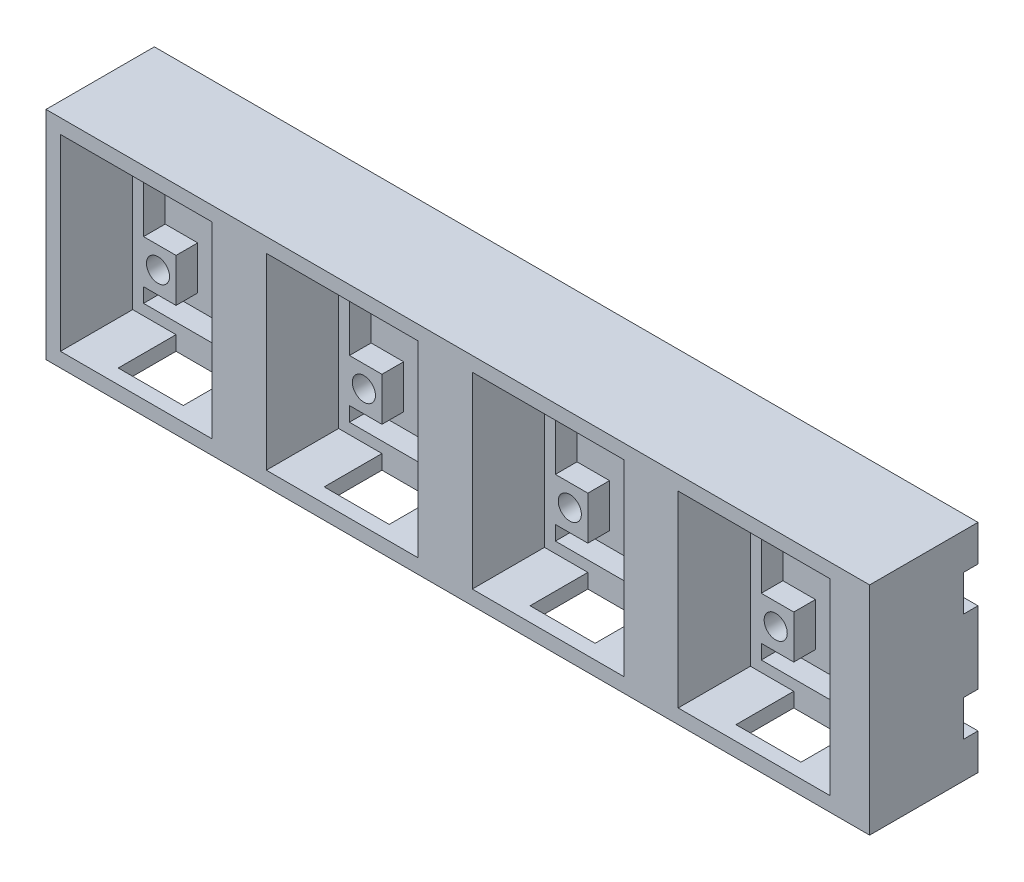
SolidWorks part; units mm, degrees
ref_plane "正面" through (0, 0, 0) normal (0, 0, 1) x (1, 0, 0)
ref_plane "平面" through (0, 0, 0) normal (0, 1, 0) x (1, 0, 0)
ref_plane "右側面" through (0, 0, 0) normal (1, 0, 0) x (0, 0, -1)
sketch "ｽｹｯﾁ1" plane through (0, 0, 0) normal (0, 0, 1) x (1, 0, 0)
  line L1 (-83.9031, 40.6786) -> (30.0969, 40.6786)
  line L2 (-83.9031, 40.6786) -> (-83.9031, 10.6786)
  line L3 (-83.9031, 10.6786) -> (30.0969, 10.6786)
  line L4 (30.0969, 40.6786) -> (30.0969, 10.6786)
  dimension "D1" = 30
extrude "ﾎﾞｽ - 押し出し1" add sketch "ｽｹｯﾁ1" along normal blind 15
sketch "ｽｹｯﾁ2" plane through (0, 0, 15) normal (0, 0, 1) x (1, 0, 0)
  line L0 (30.0969, 40.6786) -> (-83.9031, 40.6786) construction
  line L1 (-81.9031, 38.6786) -> (-60.9031, 38.6786)
  line L2 (-81.9031, 38.6786) -> (-81.9031, 12.6786)
  line L3 (-81.9031, 12.6786) -> (-60.9031, 12.6786)
  line L4 (-60.9031, 38.6786) -> (-60.9031, 12.6786)
  line L5 (-83.9031, 10.6786) -> (30.0969, 10.6786) construction
  line L7 (-83.9031, 40.6786) -> (-83.9031, 10.6786) construction
  line L8 (-58.9031, 40.6786) -> (-58.9031, 10.6786) construction
  line L9 (-55.4031, 40.6786) -> (-55.4031, 10.6786) construction
  line L10 (-30.4031, 40.6786) -> (-30.4031, 10.6786) construction
  line L11 (-26.9031, 40.6786) -> (-26.9031, 10.6786) construction
  line L12 (-1.9031, 40.6786) -> (-1.9031, 10.6786) construction
  line L13 (1.5969, 40.6786) -> (1.5969, 10.6786) construction
  line L14 (26.5969, 40.6786) -> (26.5969, 10.6786) construction
  line L16 (30.0969, 10.6786) -> (30.0969, 40.6786) construction
  line L18 (-53.4031, 38.6786) -> (-32.4031, 38.6786)
  line L19 (-53.4031, 38.6786) -> (-53.4031, 12.6786)
  line L20 (-53.4031, 12.6786) -> (-32.4031, 12.6786)
  line L21 (-32.4031, 38.6786) -> (-32.4031, 12.6786)
  line L22 (-24.9031, 38.6786) -> (-3.9031, 38.6786)
  line L23 (-24.9031, 38.6786) -> (-24.9031, 12.6786)
  line L24 (-24.9031, 12.6786) -> (-3.9031, 12.6786)
  line L25 (-3.9031, 38.6786) -> (-3.9031, 12.6786)
  line L26 (3.5969, 38.6786) -> (24.5969, 38.6786)
  line L27 (3.5969, 38.6786) -> (3.5969, 12.6786)
  line L28 (3.5969, 12.6786) -> (24.5969, 12.6786)
  line L29 (24.5969, 38.6786) -> (24.5969, 12.6786)
  dimension "D1" = 26
  dimension "D2" = 21
  dimension "D3" = 2
  dimension "D4" = 2
  dimension "D5" = 2
  dimension "D6" = 2
  dimension "D7" = 25
  dimension "D8" = 3.5
  dimension "D9" = 25
  dimension "D10" = 3.5
  dimension "D11" = 25
  dimension "D12" = 3.5
  dimension "D13" = 25
  dimension "D14" = 3.5
  dimension "D15" = 2
  dimension "D16" = 21
  dimension "D17" = 2
  dimension "D18" = 21
  dimension "D19" = 2
  dimension "D20" = 21
  dimension "D21" = 2
  dimension "D22" = 2
  dimension "D23" = 2
extrude "ｶｯﾄ - 押し出し1" cut sketch "ｽｹｯﾁ2" against normal blind 13
sketch "ｽｹｯﾁ3" plane through (0, 0, 2) normal (0, 0, 1) x (1, 0, 0)
  line L0 (-53.4031, 38.6786) -> (-53.4031, 12.6786) construction
  line L1 (-60.9031, 38.6786) -> (-81.9031, 38.6786)
  line L2 (-60.9031, 38.6786) -> (-60.9031, 12.6786)
  line L3 (-60.9031, 12.6786) -> (-81.9031, 12.6786)
  line L4 (-81.9031, 38.6786) -> (-81.9031, 12.6786)
  line L5 (-80.4031, 37.1786) -> (-62.4031, 37.1786)
  line L6 (-80.4031, 37.1786) -> (-80.4031, 14.1786)
  line L7 (-80.4031, 14.1786) -> (-62.4031, 14.1786)
  line L8 (-62.4031, 37.1786) -> (-62.4031, 14.1786)
  line L9 (-51.9031, 37.1786) -> (-33.9031, 37.1786)
  line L10 (-51.9031, 37.1786) -> (-51.9031, 14.1786)
  line L11 (-51.9031, 14.1786) -> (-33.9031, 14.1786)
  line L12 (-33.9031, 37.1786) -> (-33.9031, 14.1786)
  line L13 (-23.4031, 37.1786) -> (-5.4031, 37.1786)
  line L14 (-23.4031, 37.1786) -> (-23.4031, 14.1786)
  line L15 (-23.4031, 14.1786) -> (-5.4031, 14.1786)
  line L16 (-5.4031, 37.1786) -> (-5.4031, 14.1786)
  line L17 (5.0969, 37.1786) -> (23.0969, 37.1786)
  line L18 (5.0969, 37.1786) -> (5.0969, 14.1786)
  line L19 (5.0969, 14.1786) -> (23.0969, 14.1786)
  line L20 (23.0969, 37.1786) -> (23.0969, 14.1786)
  line L21 (-24.9031, 38.6786) -> (-24.9031, 12.6786) construction
  line L22 (3.5969, 38.6786) -> (3.5969, 12.6786) construction
  line L24 (-53.4031, 38.6786) -> (-32.4031, 38.6786)
  line L25 (-53.4031, 38.6786) -> (-53.4031, 12.6786)
  line L26 (-53.4031, 12.6786) -> (-32.4031, 12.6786)
  line L27 (-32.4031, 38.6786) -> (-32.4031, 12.6786)
  line L28 (-24.9031, 38.6786) -> (-3.9031, 38.6786)
  line L29 (-24.9031, 38.6786) -> (-24.9031, 12.6786)
  line L30 (-24.9031, 12.6786) -> (-3.9031, 12.6786)
  line L31 (-3.9031, 38.6786) -> (-3.9031, 12.6786)
  line L32 (3.5969, 38.6786) -> (24.5969, 38.6786)
  line L33 (3.5969, 38.6786) -> (3.5969, 12.6786)
  line L34 (3.5969, 12.6786) -> (24.5969, 12.6786)
  line L35 (24.5969, 38.6786) -> (24.5969, 12.6786)
  dimension "D1" = 1.5
  dimension "D2" = 1.5
  dimension "D3" = 1.5
  dimension "D4" = 1.5
  dimension "D5" = 1.5
  dimension "D6" = 1.5
  dimension "D7" = 1.5
  dimension "D8" = 26
  dimension "D9" = 21
  dimension "D10" = 26
  dimension "D11" = 21
  dimension "D12" = 26
  dimension "D13" = 21
extrude "ﾎﾞｽ - 押し出し2" add sketch "ｽｹｯﾁ3" along normal blind 3
sketch "ｽｹｯﾁ5" plane through (0, 0, 2) normal (0, 0, 1) x (1, 0, 0)
  line L0 (-62.4031, 14.1786) -> (-62.4031, 37.1786) construction
  line L1 (-62.4031, 22.1786) -> (-66.9031, 22.1786)
  line L2 (-62.4031, 22.1786) -> (-62.4031, 16.1786)
  line L3 (-62.4031, 16.1786) -> (-66.9031, 16.1786)
  line L4 (-66.9031, 22.1786) -> (-66.9031, 16.1786)
  line L5 (-51.9031, 37.1786) -> (-51.9031, 14.1786) construction
  line L6 (-81.9031, 12.6786) -> (-60.9031, 12.6786) construction
  line L7 (-80.4031, 37.1786) -> (-80.4031, 14.1786) construction
  line L8 (-80.4031, 22.1786) -> (-75.9031, 22.1786)
  line L9 (-80.4031, 22.1786) -> (-80.4031, 16.1786)
  line L10 (-80.4031, 16.1786) -> (-75.9031, 16.1786)
  line L11 (-75.9031, 22.1786) -> (-75.9031, 16.1786)
  line L12 (-51.9031, 22.1786) -> (-47.4031, 22.1786)
  line L13 (-51.9031, 22.1786) -> (-51.9031, 16.1786)
  line L14 (-51.9031, 16.1786) -> (-47.4031, 16.1786)
  line L15 (-47.4031, 22.1786) -> (-47.4031, 16.1786)
  line L16 (-33.9031, 14.1786) -> (-33.9031, 37.1786) construction
  line L17 (-33.9031, 22.1786) -> (-38.4031, 22.1786)
  line L18 (-33.9031, 22.1786) -> (-33.9031, 16.1786)
  line L19 (-33.9031, 16.1786) -> (-38.4031, 16.1786)
  line L20 (-38.4031, 22.1786) -> (-38.4031, 16.1786)
  line L21 (-23.4031, 37.1786) -> (-23.4031, 14.1786) construction
  line L22 (-23.4031, 22.1786) -> (-18.9031, 22.1786)
  line L23 (-23.4031, 22.1786) -> (-23.4031, 16.1786)
  line L24 (-23.4031, 16.1786) -> (-18.9031, 16.1786)
  line L25 (-18.9031, 22.1786) -> (-18.9031, 16.1786)
  line L26 (-5.4031, 14.1786) -> (-5.4031, 37.1786) construction
  line L27 (-5.4031, 22.1786) -> (-9.9031, 22.1786)
  line L28 (-5.4031, 22.1786) -> (-5.4031, 16.1786)
  line L29 (-5.4031, 16.1786) -> (-9.9031, 16.1786)
  line L30 (-9.9031, 22.1786) -> (-9.9031, 16.1786)
  line L31 (5.0969, 37.1786) -> (5.0969, 14.1786) construction
  line L32 (5.0969, 22.1786) -> (9.5969, 22.1786)
  line L33 (5.0969, 22.1786) -> (5.0969, 16.1786)
  line L34 (5.0969, 16.1786) -> (9.5969, 16.1786)
  line L35 (9.5969, 22.1786) -> (9.5969, 16.1786)
  line L36 (23.0969, 14.1786) -> (23.0969, 37.1786) construction
  line L37 (23.0969, 22.1786) -> (18.5969, 22.1786)
  line L38 (23.0969, 22.1786) -> (23.0969, 16.1786)
  line L39 (23.0969, 16.1786) -> (18.5969, 16.1786)
  line L40 (18.5969, 22.1786) -> (18.5969, 16.1786)
  point P10 (-66.9031, 19.1786)
  point P15 (-75.9031, 19.1786)
  dimension "D1" = 4.5
  dimension "D2" = 6
  dimension "D3" = 6.5
  dimension "D4" = 6.5
extrude "ﾎﾞｽ - 押し出し3" add sketch "ｽｹｯﾁ5" along normal blind 3
sketch "ｽｹｯﾁ6" plane through (0, 0, 5) normal (0, 0, 1) x (1, 0, 0)
  line L0 (-66.9031, 22.1786) -> (-66.9031, 16.1786) construction
  line L1 (-66.9031, 16.1786) -> (-62.4031, 16.1786) construction
  line L2 (-75.9031, 16.1786) -> (-75.9031, 22.1786) construction
  line L3 (-80.4031, 16.1786) -> (-75.9031, 16.1786) construction
  line L4 (-47.4031, 16.1786) -> (-47.4031, 22.1786) construction
  line L5 (-51.9031, 16.1786) -> (-47.4031, 16.1786) construction
  line L6 (-38.4031, 22.1786) -> (-38.4031, 16.1786) construction
  line L7 (-38.4031, 16.1786) -> (-33.9031, 16.1786) construction
  line L8 (-18.9031, 16.1786) -> (-18.9031, 22.1786) construction
  line L9 (-23.4031, 16.1786) -> (-18.9031, 16.1786) construction
  line L10 (-9.9031, 22.1786) -> (-9.9031, 16.1786) construction
  line L11 (-9.9031, 16.1786) -> (-5.4031, 16.1786) construction
  line L12 (9.5969, 16.1786) -> (9.5969, 22.1786) construction
  line L13 (5.0969, 16.1786) -> (9.5969, 16.1786) construction
  line L14 (18.5969, 22.1786) -> (18.5969, 16.1786) construction
  line L15 (18.5969, 16.1786) -> (23.0969, 16.1786) construction
  circle A0 centre (-64.4031, 19.1786) radius 1.6
  circle A1 centre (-78.4031, 19.1786) radius 1.6
  circle A2 centre (-49.9031, 19.1786) radius 1.6
  circle A3 centre (-35.9031, 19.1786) radius 1.6
  circle A4 centre (-21.4031, 19.1786) radius 1.6
  circle A5 centre (-7.4031, 19.1786) radius 1.6
  circle A6 centre (7.0969, 19.1786) radius 1.6
  circle A7 centre (21.0969, 19.1786) radius 1.6
  dimension "D1" = 3.2
  dimension "D4" = 2.5
  dimension "D5" = 3
  dimension "D6" = 2.5
  dimension "D2" = 2.5
  dimension "D3" = 3
  dimension "D7" = 3
  dimension "D8" = 2.5
  dimension "D9" = 3
  dimension "D10" = 2.5
  dimension "D11" = 3
  dimension "D12" = 2.5
  dimension "D13" = 3
  dimension "D14" = 2.5
  dimension "D15" = 3
  dimension "D16" = 2.5
  dimension "D17" = 3
extrude "ｶｯﾄ - 押し出し2" cut sketch "ｽｹｯﾁ6" against normal through all
sketch "ｽｹｯﾁ7" plane through (0, 12.6786, 0) normal (0, 1, 0) x (1, 0, 0)
  line L0 (-81.9031, -5) -> (-60.9031, -5) construction
  line L1 (-66.9031, -5) -> (-75.9031, -5)
  line L2 (-66.9031, -5) -> (-66.9031, -13)
  line L3 (-66.9031, -13) -> (-75.9031, -13)
  line L4 (-75.9031, -5) -> (-75.9031, -13)
  line L5 (-81.9031, -15) -> (-60.9031, -15) construction
  line L6 (-60.9031, -5) -> (-60.9031, -15) construction
  line L7 (-81.9031, -5) -> (-81.9031, -15) construction
  line L8 (-53.4031, -5) -> (-32.4031, -5) construction
  line L9 (-38.4031, -5) -> (-47.4031, -5)
  line L10 (-38.4031, -5) -> (-38.4031, -13)
  line L11 (-38.4031, -13) -> (-47.4031, -13)
  line L12 (-47.4031, -5) -> (-47.4031, -13)
  line L13 (-24.9031, -5) -> (-3.9031, -5) construction
  line L14 (-9.9031, -5) -> (-18.9031, -5)
  line L15 (-9.9031, -5) -> (-9.9031, -13)
  line L16 (-9.9031, -13) -> (-18.9031, -13)
  line L17 (-18.9031, -5) -> (-18.9031, -13)
  line L18 (3.5969, -5) -> (24.5969, -5) construction
  line L19 (18.5969, -5) -> (9.5969, -5)
  line L20 (18.5969, -5) -> (18.5969, -13)
  line L21 (18.5969, -13) -> (9.5969, -13)
  line L22 (9.5969, -5) -> (9.5969, -13)
  line L23 (-53.4031, -5) -> (-53.4031, -15) construction
  line L24 (-24.9031, -5) -> (-24.9031, -15) construction
  line L25 (3.5969, -5) -> (3.5969, -15) construction
  dimension "D1" = 2
  dimension "D2" = 6
  dimension "D3" = 6
  dimension "D4" = 8
  dimension "D5" = 9
  dimension "D6" = 8
  dimension "D7" = 9
  dimension "D8" = 8
  dimension "D9" = 9
  dimension "D10" = 6
  dimension "D11" = 6
  dimension "D12" = 6
extrude "ｶｯﾄ - 押し出し3" cut sketch "ｽｹｯﾁ7" against normal through all
sketch "ｽｹｯﾁ12" plane through (30.0969, 0, 0) normal (1, 0, 0) x (0, 0, -1)
  line L0 (0, 10.6786) -> (0, 40.6786) construction
  line L1 (0, 15.6786) -> (-2, 15.6786)
  line L2 (0, 15.6786) -> (0, 20.6786)
  line L3 (0, 20.6786) -> (-2, 20.6786)
  line L4 (-2, 15.6786) -> (-2, 20.6786)
  line L5 (-15, 10.6786) -> (0, 10.6786) construction
  line L6 (0, 30.6786) -> (-2, 30.6786)
  line L7 (0, 30.6786) -> (0, 35.6786)
  line L8 (0, 35.6786) -> (-2, 35.6786)
  line L9 (-2, 30.6786) -> (-2, 35.6786)
  line L10 (-15, 40.6786) -> (0, 40.6786) construction
  dimension "D1" = 5
  dimension "D2" = 5
  dimension "D3" = 5
  dimension "D4" = 5
  dimension "D5" = 2
  dimension "D6" = 2
extrude "ｶｯﾄ - 押し出し4" cut sketch "ｽｹｯﾁ12" against normal blind 3.5
